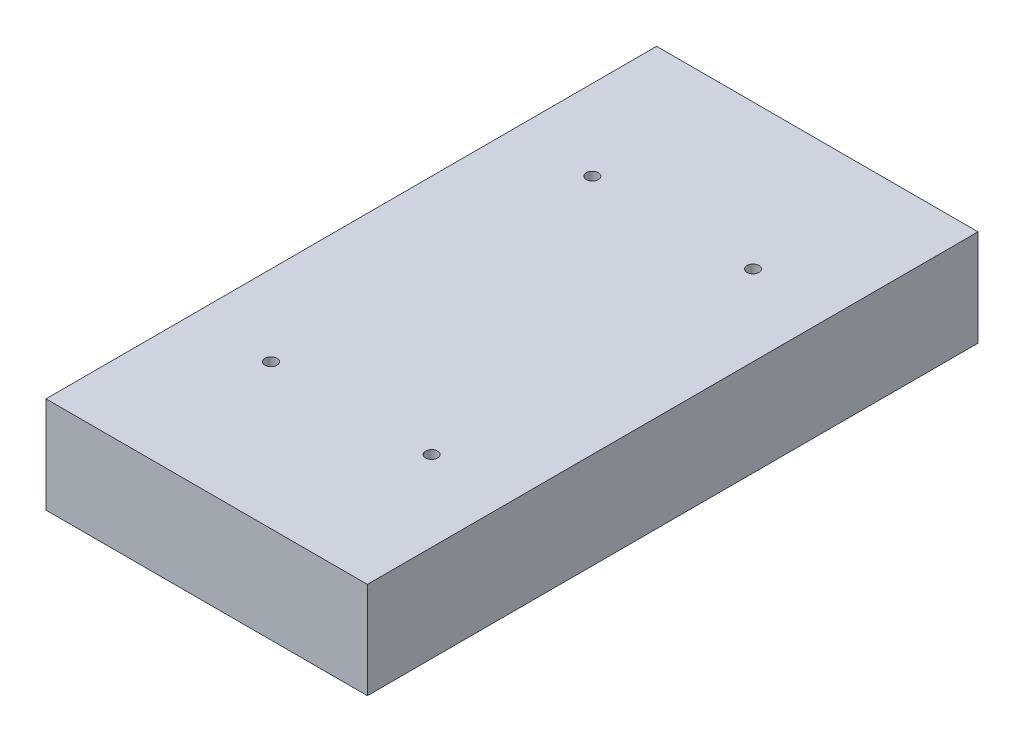
SolidWorks part; units mm, degrees
ref_plane "Front Plane" through (0, 0, 0) normal (0, 0, 1) x (1, 0, 0)
ref_plane "Top Plane" through (0, 0, 0) normal (0, 1, 0) x (1, 0, 0)
ref_plane "Right Plane" through (0, 0, 0) normal (1, 0, 0) x (0, 0, -1)
sketch "Sketch1" plane through (0, 0, 0) normal (0, 1, 0) x (1, 0, 0)
  line L1 (-254, 482.6) -> (254, 482.6)
  line L2 (-254, 482.6) -> (-254, -482.6)
  line L3 (-254, -482.6) -> (254, -482.6)
  line L4 (254, 482.6) -> (254, -482.6)
  line L5 (-254, 482.6) -> (254, -482.6) construction
  line L6 (-254, -482.6) -> (254, 482.6) construction
  point P0 (0, 0)
  dimension "D1" = 965.2
  dimension "D2" = 508
extrude "Boss-Extrude1" add sketch "Sketch1" along normal blind 152.4 contours L2 L3 L4 L1
sketch "Sketch2" plane through (0, 152.4, 0) normal (0, 1, 0) x (1, 0, 0)
  line L0 (0, 0) -> (0, 500.9377) construction
  line L1 (0, 0) -> (443.0604, 0) construction
  circle A0 centre (127, 254) radius 9.525
  circle A1 centre (-127, 254) radius 9.525
  circle A2 centre (127, -254) radius 9.525
  circle A3 centre (-127, -254) radius 9.525
  dimension "D1" = 19.05
  dimension "D2" = 127
  dimension "D3" = 254
extrude "Cut-Extrude1" cut sketch "Sketch2" against normal blind 127
